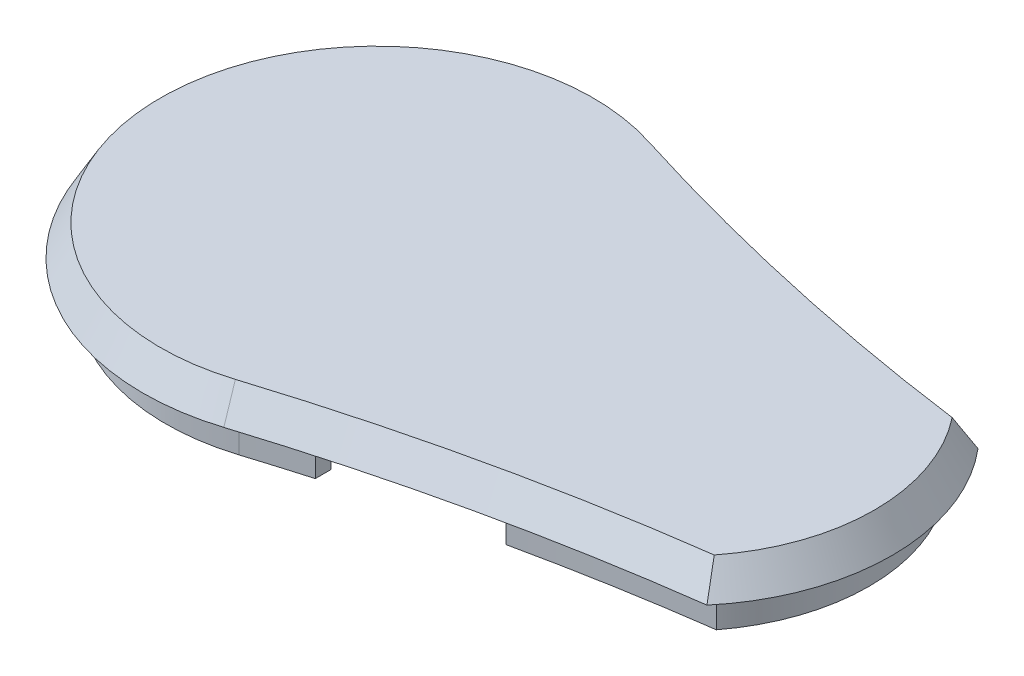
SolidWorks part; units mm, degrees
ref_plane "Front Plane" through (0, 0, 0) normal (0, 0, 1) x (1, 0, 0)
ref_plane "Top Plane" through (0, 0, 0) normal (0, 1, 0) x (1, 0, 0)
ref_plane "Right Plane" through (0, 0, 0) normal (1, 0, 0) x (0, 0, -1)
sketch "Sketch1" plane through (0, 0, 0) normal (0, 1, 0) x (1, 0, 0)
  line L0 (32, 19.94) -> (31.4045, 20.5355) construction
  line L1 (27.869, 22) -> (23.5611, 22) construction
  line L2 (23.5611, -22) -> (27.869, -22) construction
  line L3 (31.4045, -20.5355) -> (32, -19.94) construction
  arc A0 (8.2975, 26.3747) -> (8.2975, -26.3747) centre (0, 0) ccw construction
  arc A1 (9.1978, 29.2365) -> (9.1978, -29.2365) centre (0, 0) ccw
  arc A2 (61.0069, -17.7555) -> (9.1978, -29.2365) centre (101.1333, -321.467) ccw
  arc A3 (61.0069, -17.7555) -> (61.0069, 17.7555) centre (40, 0) ccw
  arc A4 (9.1978, 29.2365) -> (61.0069, 17.7555) centre (101.1333, 321.467) ccw
  arc A5 (59.4238, -14.9409) -> (59.4238, 14.9409) centre (40, 0) ccw construction
  arc A6 (32, 19.94) -> (59.4238, 14.9409) centre (101.1333, 321.467) ccw construction
  arc A7 (31.4045, 20.5355) -> (27.869, 22) centre (27.869, 17) ccw construction
  arc A8 (8.2975, 26.3747) -> (23.5611, 22) centre (101.1333, 321.467) ccw construction
  arc A9 (23.5611, -22) -> (8.2975, -26.3747) centre (101.1333, -321.467) ccw construction
  arc A10 (27.869, -22) -> (31.4045, -20.5355) centre (27.869, -17) ccw construction
  arc A11 (59.4238, -14.9409) -> (32, -19.94) centre (101.1333, -321.467) ccw construction
extrude "Boss-Extrude1" add sketch "Sketch1" along normal blind 4 draft 30
sketch "Sketch2" plane through (0, 0, 0) normal (0, -1, 0) x (1, 0, 0)
  line L0 (27.869, -22) -> (23.5611, -22) construction
  line L1 (32, -19.94) -> (31.4045, -20.5355) construction
  line L2 (31.4045, 20.5355) -> (32, 19.94) construction
  line L3 (23.5611, 22) -> (27.869, 22) construction
  line L4 (27.869, -22) -> (23.5611, -22)
  line L5 (32, -19.94) -> (31.4045, -20.5355)
  line L6 (31.4045, 20.5355) -> (32, 19.94)
  line L7 (23.5611, 22) -> (27.869, 22)
  line L8 (27.869, -20) -> (23.3067, -20)
  line L9 (23.3067, 20) -> (27.869, 20)
  line L10 (29.9903, 19.1213) -> (30.9918, 18.1198)
  line L11 (30.9918, -18.1198) -> (29.9903, -19.1213)
  arc A0 (8.2975, 26.3747) -> (8.2975, -26.3747) centre (0, 0) ccw construction
  arc A1 (8.2975, 26.3747) -> (8.2975, -26.3747) centre (0, 0) ccw
  arc A2 (23.5611, -22) -> (8.2975, -26.3747) centre (101.1333, -321.467) ccw construction
  arc A3 (27.869, -22) -> (31.4045, -20.5355) centre (27.869, -17) ccw construction
  arc A4 (59.4238, -14.9409) -> (32, -19.94) centre (101.1333, -321.467) ccw construction
  arc A5 (59.4238, -14.9409) -> (59.4238, 14.9409) centre (40, 0) ccw construction
  arc A6 (32, 19.94) -> (59.4238, 14.9409) centre (101.1333, 321.467) ccw construction
  arc A7 (31.4045, 20.5355) -> (27.869, 22) centre (27.869, 17) ccw construction
  arc A8 (8.2975, 26.3747) -> (23.5611, 22) centre (101.1333, 321.467) ccw construction
  arc A9 (23.5611, -22) -> (8.2975, -26.3747) centre (101.1333, -321.467) ccw
  arc A10 (27.869, -22) -> (31.4045, -20.5355) centre (27.869, -17) ccw
  arc A11 (59.4238, -14.9409) -> (32, -19.94) centre (101.1333, -321.467) ccw
  arc A12 (59.4238, -14.9409) -> (59.4238, 14.9409) centre (40, 0) ccw
  arc A13 (32, 19.94) -> (59.4238, 14.9409) centre (101.1333, 321.467) ccw
  arc A14 (31.4045, 20.5355) -> (27.869, 22) centre (27.869, 17) ccw
  arc A15 (8.2975, 26.3747) -> (23.5611, 22) centre (101.1333, 321.467) ccw
  arc A16 (23.3067, -20) -> (7.6973, -24.4669) centre (101.1333, -321.467) ccw
  arc A17 (7.6973, 24.4669) -> (7.6973, -24.4669) centre (0, 0) ccw
  arc A18 (7.6973, 24.4669) -> (23.3067, 20) centre (101.1333, 321.467) ccw
  arc A19 (29.9903, 19.1213) -> (27.869, 20) centre (27.869, 17) ccw
  arc A20 (30.9918, 18.1198) -> (58.3183, 13.074) centre (101.1333, 321.467) ccw
  arc A21 (58.3183, -13.074) -> (58.3183, 13.074) centre (40, 0) ccw
  arc A22 (58.3183, -13.074) -> (30.9918, -18.1198) centre (101.1333, -321.467) ccw
  arc A23 (27.869, -20) -> (29.9903, -19.1213) centre (27.869, -17) ccw
  dimension "D1" = 2
extrude "Boss-Extrude2" add sketch "Sketch2" along normal blind 5
sketch "Sketch3" plane through (0, 0, 0) normal (0, -1, 0) x (1, 0, 0)
  line L4 (23.3067, -20) -> (27.869, -20)
  line L5 (29.9903, -19.1213) -> (30.9918, -18.1198)
  line L6 (30.9918, 18.1198) -> (29.9903, 19.1213)
  line L7 (27.869, 20) -> (23.3067, 20)
  line L8 (23.3067, -20) -> (27.869, -20)
  line L9 (29.9903, -19.1213) -> (30.9918, -18.1198)
  line L10 (30.9918, 18.1198) -> (29.9903, 19.1213)
  line L11 (27.869, 20) -> (23.3067, 20)
  arc A8 (27.869, -20) -> (29.9903, -19.1213) centre (27.869, -17) ccw
  arc A9 (58.3183, -13.074) -> (30.9918, -18.1198) centre (101.1333, -321.467) ccw
  arc A10 (58.3183, -13.074) -> (58.3183, 13.074) centre (40, 0) ccw
  arc A11 (30.9918, 18.1198) -> (58.3183, 13.074) centre (101.1333, 321.467) ccw
  arc A12 (29.9903, 19.1213) -> (27.869, 20) centre (27.869, 17) ccw
  arc A13 (7.6973, 24.4669) -> (23.3067, 20) centre (101.1333, 321.467) ccw
  arc A14 (7.6973, 24.4669) -> (7.6973, -24.4669) centre (0, 0) ccw
  arc A15 (23.3067, -20) -> (7.6973, -24.4669) centre (101.1333, -321.467) ccw
  arc A16 (27.869, -20) -> (29.9903, -19.1213) centre (27.869, -17) ccw
  arc A17 (58.3183, -13.074) -> (30.9918, -18.1198) centre (101.1333, -321.467) ccw
  arc A18 (58.3183, -13.074) -> (58.3183, 13.074) centre (40, 0) ccw
  arc A19 (30.9918, 18.1198) -> (58.3183, 13.074) centre (101.1333, 321.467) ccw
  arc A20 (29.9903, 19.1213) -> (27.869, 20) centre (27.869, 17) ccw
  arc A21 (7.6973, 24.4669) -> (23.3067, 20) centre (101.1333, 321.467) ccw
  arc A22 (7.6973, 24.4669) -> (7.6973, -24.4669) centre (0, 0) ccw
  arc A23 (23.3067, -20) -> (7.6973, -24.4669) centre (101.1333, -321.467) ccw
  dimension "D1" = 0
extrude "Cut-Extrude1" cut sketch "Sketch3" against normal blind 2
sketch "Sketch4" plane through (0, -5, 0) normal (0, -1, 0) x (1, 0, 0)
  line L0 (0, 0) -> (62.5054, 0) construction
  line L1 (16, 32.5) -> (16, -32.5)
  line L2 (36, 32.5) -> (36, -32.5)
  line L3 (16, 32.5) -> (36, 32.5)
  line L4 (16, -32.5) -> (36, -32.5)
  arc A0 (58.3183, -13.074) -> (58.3183, 13.074) centre (40, 0) ccw construction
  point P10 (16, 0)
  dimension "D1" = 65
  dimension "D2" = 20
  dimension "D3" = 16
extrude "Cut-Extrude2" cut sketch "Sketch4" against normal up to surface (5 mm away) up to face at (26.6407, 0, 0)
